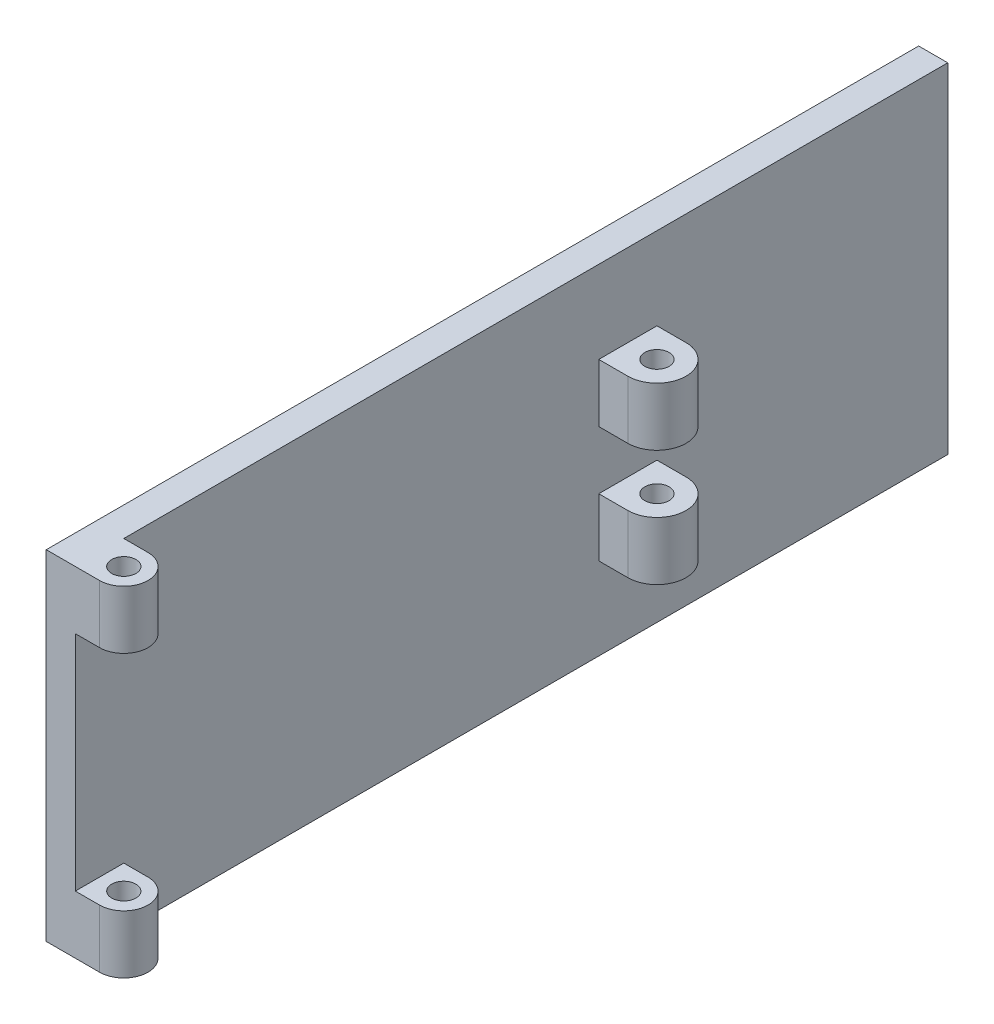
SolidWorks part; units mm, degrees
ref_plane "Спереди" through (0, 0, 0) normal (0, 0, 1) x (1, 0, 0)
ref_plane "Сверху" through (0, 0, 0) normal (0, 1, 0) x (1, 0, 0)
ref_plane "Справа" through (0, 0, 0) normal (1, 0, 0) x (0, 0, -1)
sketch "Эскиз1" plane through (0, 0, 0) normal (1, 0, 0) x (0, 0, -1)
  line L1 (0, 0) -> (90, 0)
  line L2 (0, 0) -> (0, 35)
  line L3 (0, 35) -> (90, 35)
  line L4 (90, 0) -> (90, 35)
  dimension "D1" = 35
  dimension "D2" = 90
extrude "Бобышка-Вытянуть1" add sketch "Эскиз1" along normal blind 3
sketch "Эскиз2" plane through (3, 0, 0) normal (1, 0, 0) x (0, 0, -1)
  line L1 (0, 35) -> (5, 35)
  line L2 (0, 35) -> (0, 29)
  line L3 (0, 29) -> (5, 29)
  line L4 (5, 35) -> (5, 29)
  line L5 (0, 0) -> (5, 0)
  line L6 (0, 0) -> (0, 6)
  line L7 (0, 6) -> (5, 6)
  line L8 (5, 0) -> (5, 6)
  dimension "D1" = 6
  dimension "D2" = 6
  dimension "D3" = 5
  dimension "D4" = 5
extrude "Бобышка-Вытянуть2" add sketch "Эскиз2" along normal blind 5
sketch "Эскиз3" plane through (0, 0, 0) normal (0, -1, 0) x (-1, 0, 0)
  line L1 (-8, 5) -> (-3, 5) construction
  line L2 (-8, 0) -> (0, 0) construction
  line L3 (-8, 0) -> (-8, 5) construction
  line L4 (-5.5, 0) -> (-8, 0)
  line L5 (-8, 0) -> (-8, 5)
  line L6 (-8, 5) -> (-5.5, 5)
  circle A0 centre (-5.5, 2.5) radius 2.5
  circle A1 centre (-5.5, 2.5) radius 1.25
  line M4 (-3, 5) -> (-8, 5)
  line M5 (-8, 5) -> (-8, 0)
  line M6 (-8, 0) -> (0, 0)
  dimension "D1" = 2.5
extrude "Вырез-Вытянуть1" cut sketch "Эскиз3" against normal through all contours A1 | A0 M4 M5 | A0 L5 M6
sketch "Эскиз4" plane through (3, 0, 0) normal (1, 0, 0) x (0, 0, -1)
  line L1 (54, 26.5) -> (60, 26.5)
  line L2 (54, 26.5) -> (54, 20.5)
  line L3 (54, 20.5) -> (60, 20.5)
  line L4 (60, 26.5) -> (60, 20.5)
  line L5 (0, 17.5) -> (90, 17.5) construction
  line L6 (54, 14.5) -> (60, 14.5)
  line L7 (54, 14.5) -> (54, 8.5)
  line L8 (54, 8.5) -> (60, 8.5)
  line L9 (60, 14.5) -> (60, 8.5)
  line L10 (0, 29) -> (0, 6) construction
  line L11 (90, 0) -> (90, 35) construction
  line L12 (54, 20.5) -> (54, 17.5) construction
  line L13 (54, 17.5) -> (54, 14.5) construction
  dimension "D1" = 6
  dimension "D2" = 6
  dimension "D3" = 6
  dimension "D4" = 30
extrude "Бобышка-Вытянуть3" add sketch "Эскиз4" along normal blind 6
sketch "Эскиз5" plane through (0, 8.5, 0) normal (0, -1, 0) x (-1, 0, 0)
  line L0 (-9, 54) -> (-9, 60) construction
  line L1 (-9, 60) -> (-3, 60) construction
  line L2 (-9, 54) -> (-3, 54) construction
  line L3 (-6, 54) -> (-9, 54)
  line L4 (-9, 54) -> (-9, 60)
  line L5 (-9, 60) -> (-6, 60)
  circle A0 centre (-6, 57) radius 3
  circle A1 centre (-6, 57) radius 1.25
  line M2 (-3, 60) -> (-9, 60)
  line M3 (-9, 60) -> (-9, 54)
  line M4 (-9, 54) -> (-3, 54)
  dimension "D1" = 2.5
extrude "Вырез-Вытянуть2" cut sketch "Эскиз5" against normal through all and the other way through all contours A1 | A0 M2 M3 | A0 L4 M4
